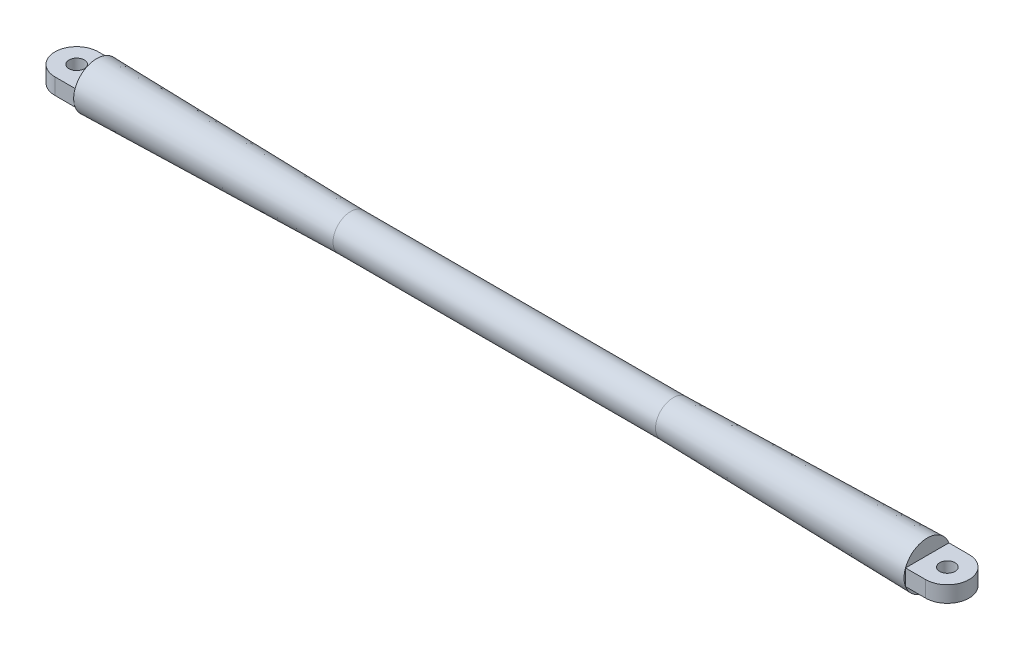
SolidWorks part; units mm, degrees
ref_plane "Front Plane" through (0, 0, 0) normal (0, 0, 1) x (1, 0, 0)
ref_plane "Top Plane" through (0, 0, 0) normal (0, 1, 0) x (1, 0, 0)
ref_plane "Right Plane" through (0, 0, 0) normal (1, 0, 0) x (0, 0, -1)
sketch "Sketch1" plane through (0, 0, 0) normal (0, 1, 0) x (1, 0, 0)
  line L0 (0, 0) -> (575, 0)
  line L1 (575, 0) -> (575, 30)
  line L2 (575, 30) -> (200, 22)
  line L3 (200, 22) -> (0, 22)
  line L4 (0, 22) -> (0, 0)
  dimension "D1" = 575
  dimension "D2" = 30
  dimension "D3" = 200
  dimension "D4" = 22
revolve "Revolve1" add sketch "Sketch1" angle 360 about L0
sketch "Sketch2" plane through (0, 0, 0) normal (0, 0, 1) x (1, 0, 0)
  line L0 (575, 0) -> (644.3876, 0) construction
  line L1 (515, 78.0386) -> (616.6682, 78.0386)
  line L2 (515, 78.0386) -> (515, 10)
  line L3 (515, 10) -> (616.6682, 10)
  line L4 (616.6682, 78.0386) -> (616.6682, 10)
  line L5 (575, -30) -> (575, 30) construction
  line L6 (515, -78.0386) -> (515, -10)
  line L7 (515, -78.0386) -> (616.6682, -78.0386)
  line L8 (616.6682, -78.0386) -> (616.6682, -10)
  line L9 (515, -10) -> (616.6682, -10)
  dimension "D1" = 10
  dimension "D2" = 60
extrude "Cut-Extrude1" cut sketch "Sketch2" against normal mid plane 190
sketch "Sketch3" plane through (0, 10, 0) normal (0, 1, 0) x (1, 0, 0)
  line L0 (515, 26.9228) -> (540, 26.9228)
  line L1 (540, -26.9228) -> (515, -26.9228)
  line L2 (515, 26.9228) -> (515, 50.7384)
  line L3 (515, 50.7384) -> (582.6602, 50.7384)
  line L4 (582.6602, 50.7384) -> (582.6602, -41.5076)
  line L5 (582.6602, -41.5076) -> (515, -41.5076)
  line L6 (515, -41.5076) -> (515, -26.9228)
  arc A0 (540, 26.9228) -> (540, -26.9228) centre (540, 0) cw
  dimension "D1" = 25
extrude "Cut-Extrude2" cut sketch "Sketch3" against normal mid plane 310
sketch "Sketch4" plane through (0, 10, 0) normal (0, 1, 0) x (1, 0, 0)
  circle A0 centre (540, 0) radius 9.5
  dimension "D1" = 19
extrude "Cut-Extrude3" cut sketch "Sketch4" against normal through all
mirror "Mirror1" about plane through (0, 0, -22) normal (1, 0, 0) of bodies 104
